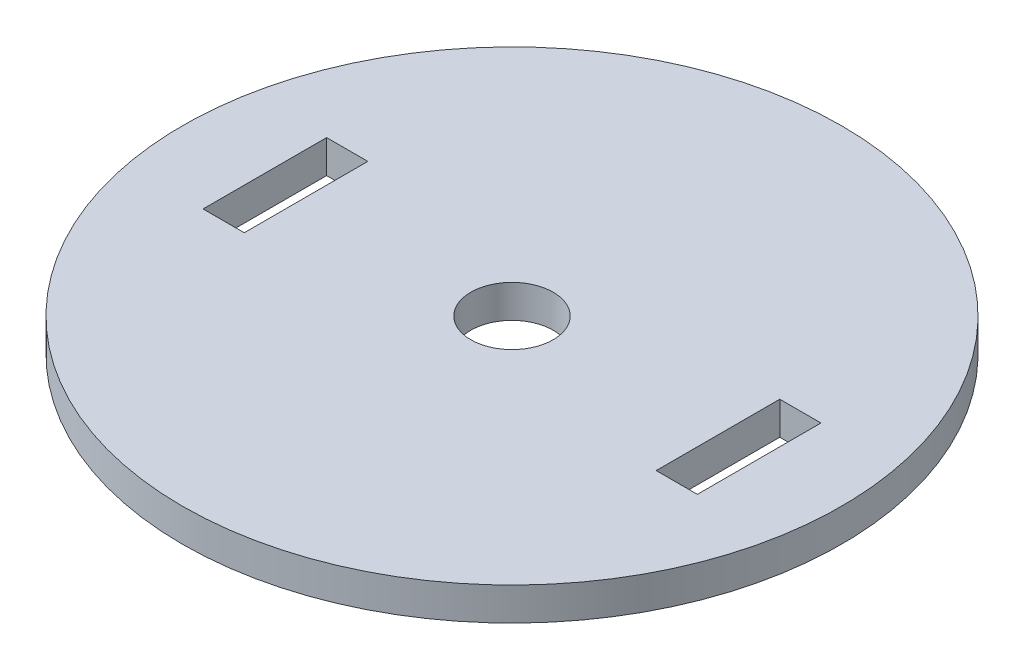
SolidWorks part; units mm, degrees
material "Cedar"
ref_plane "Front Plane" through (0, 0, 0) normal (0, 0, 1) x (1, 0, 0)
ref_plane "Top Plane" through (0, 0, 0) normal (0, 1, 0) x (1, 0, 0)
ref_plane "Right Plane" through (0, 0, 0) normal (1, 0, 0) x (0, 0, -1)
sketch "Sketch1" plane through (0, 0, 0) normal (0, 1, 0) x (1, 0, 0)
  circle A0 centre (0, 0) radius 40
  circle A1 centre (0, 0) radius 5
  dimension "D1" = 80
  dimension "D2" = 10
extrude "Boss-Extrude1" add sketch "Sketch1" along normal blind 4
sketch "Sketch2" plane through (0, 4, 0) normal (0, 1, 0) x (1, 0, 0)
  line L0 (-40, 0) -> (40, 0) construction
  line L2 (-30, -7.5) -> (-25, -7.5)
  line L3 (-30, -7.5) -> (-30, 7.5)
  line L4 (-30, 7.5) -> (-25, 7.5)
  line L5 (-25, -7.5) -> (-25, 7.5)
  line L6 (-30, -7.5) -> (-25, 7.5) construction
  line L7 (-30, 7.5) -> (-25, -7.5) construction
  circle A0 centre (0, 0) radius 40 construction
  circle A1 centre (0, 0) radius 5 construction
  point P5 (-27.5, 0)
  dimension "D1" = 15
  dimension "D2" = 5
  dimension "D3" = 30
extrude "Cut-Extrude1" cut sketch "Sketch2" against normal blind 4
mirror "Mirror1" about plane through (0, 0, 0) normal (1, 0, 0) of "Cut-Extrude1"
